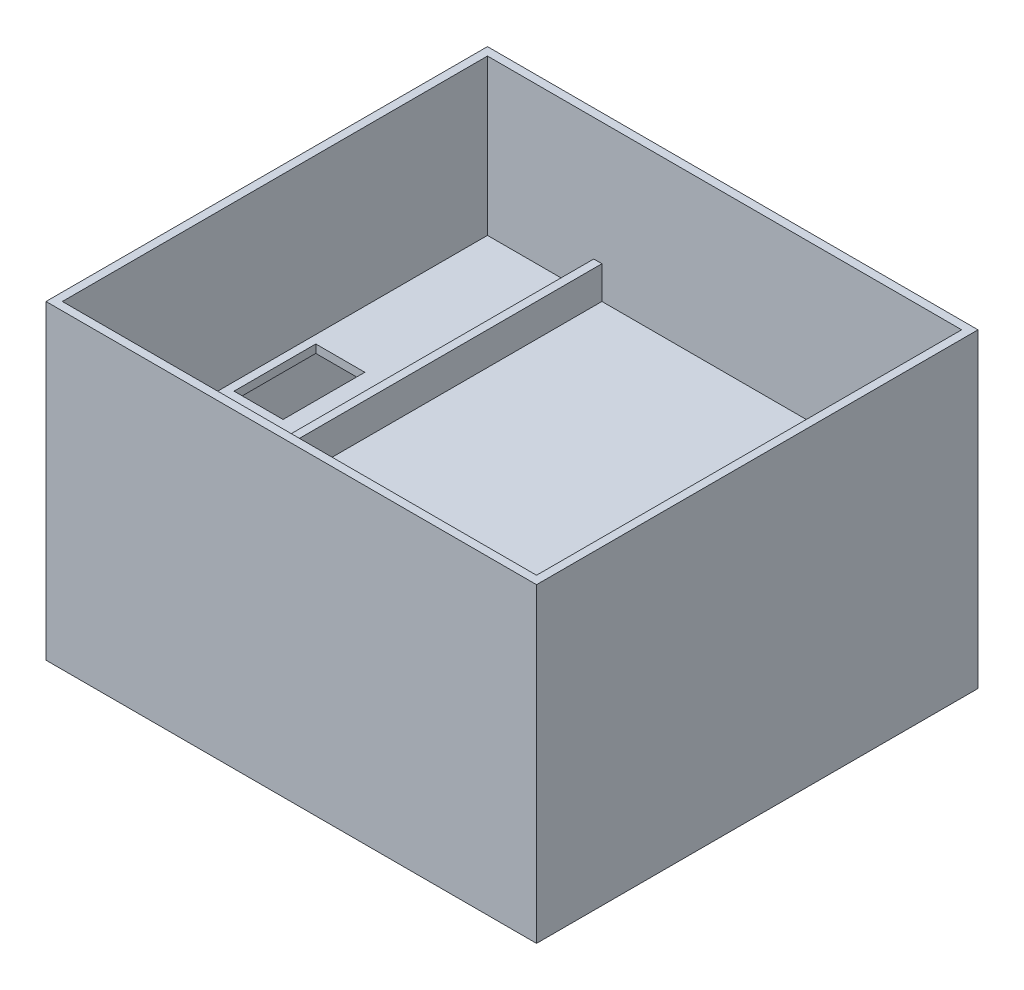
SolidWorks part; units mm, degrees
ref_plane "Front Plane" through (0, 0, 0) normal (0, 0, 1) x (1, 0, 0)
ref_plane "Top Plane" through (0, 0, 0) normal (0, 1, 0) x (1, 0, 0)
ref_plane "Right Plane" through (0, 0, 0) normal (1, 0, 0) x (0, 0, -1)
sketch "Sketch1" plane through (0, 0, 0) normal (0, 1, 0) x (1, 0, 0)
  line L1 (-113.8745, -60.9464) -> (-53.8745, -60.9464)
  line L2 (-113.8745, -60.9464) -> (-113.8745, -6.9464)
  line L3 (-113.8745, -6.9464) -> (-53.8745, -6.9464)
  line L4 (-53.8745, -60.9464) -> (-53.8745, -6.9464)
  dimension "D1" = 60
  dimension "D2" = 54
extrude "Boss-Extrude1" add sketch "Sketch1" along normal blind 38
sketch "Sketch2" plane through (0, 38, 0) normal (0, 1, 0) x (1, 0, 0)
  line L0 (-53.8745, -60.9464) -> (-53.8745, -6.9464) construction
  line L1 (-54.8745, -7.9464) -> (-98.8745, -7.9464)
  line L2 (-54.8745, -7.9464) -> (-54.8745, -59.9464)
  line L3 (-54.8745, -59.9464) -> (-98.8745, -59.9464)
  line L4 (-98.8745, -7.9464) -> (-98.8745, -59.9464)
  line L5 (-53.8745, -6.9464) -> (-113.8745, -6.9464) construction
  line L6 (-113.8745, -60.9464) -> (-53.8745, -60.9464) construction
  dimension "D1" = 1
  dimension "D2" = 1
  dimension "D3" = 1
  dimension "D4" = 44
extrude "Cut-Extrude1" cut sketch "Sketch2" against normal blind 19
sketch "Sketch3" plane through (0, 0, 0) normal (0, -1, 0) x (-1, 0, 0)
  line L0 (113.8745, -60.9464) -> (53.8745, -60.9464) construction
  line L1 (112.8745, -59.9464) -> (77.8745, -59.9464)
  line L2 (112.8745, -59.9464) -> (112.8745, -7.9464)
  line L3 (112.8745, -7.9464) -> (77.8745, -7.9464)
  line L4 (77.8745, -59.9464) -> (77.8745, -7.9464)
  line L5 (113.8745, -6.9464) -> (113.8745, -60.9464) construction
  line L6 (53.8745, -6.9464) -> (113.8745, -6.9464) construction
  dimension "D1" = 1
  dimension "D2" = 35
  dimension "D3" = 1
  dimension "D4" = 1
extrude "Cut-Extrude2" cut sketch "Sketch3" against normal blind 18
sketch "Sketch4" plane through (0, 18, 0) normal (0, -1, 0) x (-1, 0, 0)
  line L0 (77.8745, -59.9464) -> (112.8745, -59.9464) construction
  line L1 (111.8745, -39.9464) -> (105.8745, -39.9464)
  line L2 (111.8745, -39.9464) -> (111.8745, -29.9464)
  line L3 (111.8745, -29.9464) -> (105.8745, -29.9464)
  line L4 (105.8745, -39.9464) -> (105.8745, -29.9464)
  line L5 (112.8745, -7.9464) -> (77.8745, -7.9464) construction
  line L6 (112.8745, -59.9464) -> (112.8745, -7.9464) construction
  dimension "D1" = 20
  dimension "D2" = 22
  dimension "D3" = 1
  dimension "D4" = 6
extrude "Cut-Extrude3" cut sketch "Sketch4" against normal blind 38
sketch "Sketch5" plane through (0, 38, 0) normal (0, 1, 0) x (1, 0, 0)
  line L0 (-53.8745, -6.9464) -> (-113.8745, -6.9464) construction
  line L1 (-98.8745, -59.9464) -> (-112.8745, -59.9464)
  line L2 (-98.8745, -59.9464) -> (-98.8745, -7.9464)
  line L3 (-98.8745, -7.9464) -> (-112.8745, -7.9464)
  line L4 (-112.8745, -59.9464) -> (-112.8745, -7.9464)
  line L5 (-113.8745, -6.9464) -> (-113.8745, -60.9464) construction
  dimension "D1" = 1
  dimension "D2" = 1
extrude "Cut-Extrude5" cut sketch "Sketch5" against normal blind 15
sketch "Sketch6" plane through (0, 23, 0) normal (0, 1, 0) x (1, 0, 0)
  line L0 (-112.8745, -59.9464) -> (-98.8745, -59.9464) construction
  line L1 (-112.8745, -7.9464) -> (-99.8745, -7.9464)
  line L2 (-112.8745, -7.9464) -> (-112.8745, -59.9464)
  line L3 (-112.8745, -59.9464) -> (-99.8745, -59.9464)
  line L4 (-99.8745, -7.9464) -> (-99.8745, -59.9464)
  line L5 (-98.8745, -59.9464) -> (-98.8745, -7.9464) construction
  dimension "D1" = 1
extrude "Cut-Extrude6" cut sketch "Sketch6" against normal blind 4
